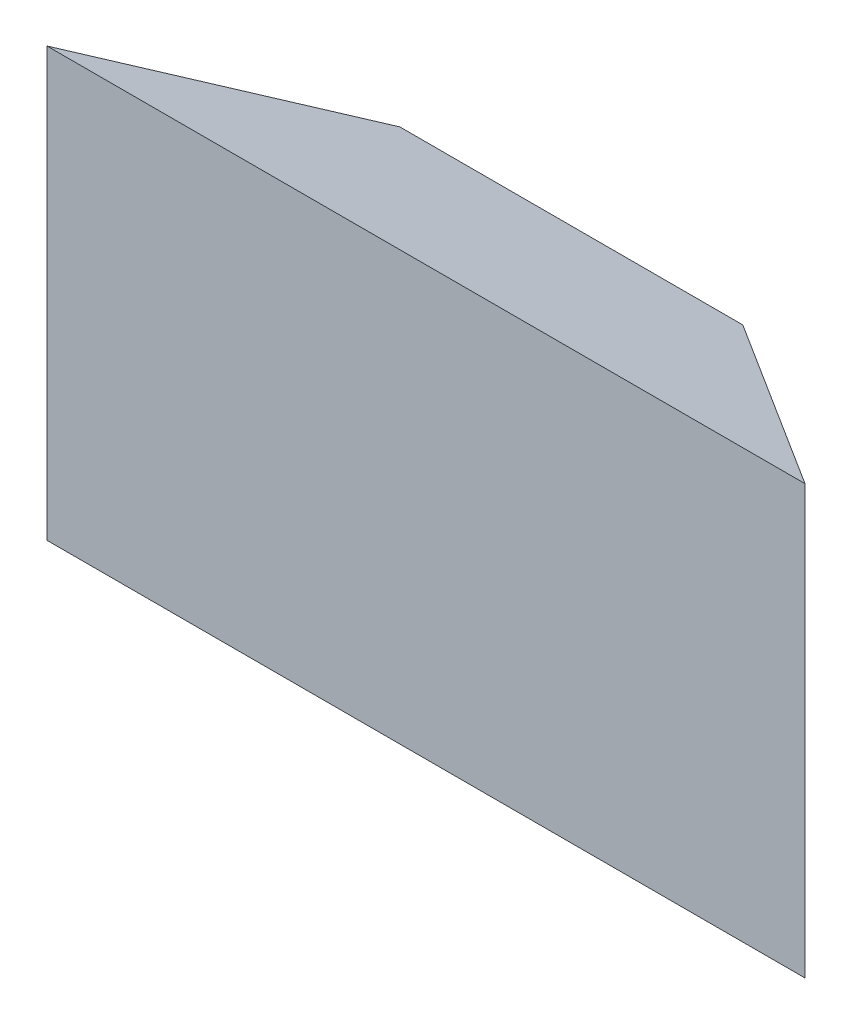
SolidWorks part; units mm, degrees
ref_plane "前视基准面" through (0, 0, 0) normal (0, 0, 1) x (1, 0, 0)
ref_plane "上视基准面" through (0, 0, 0) normal (0, 1, 0) x (1, 0, 0)
ref_plane "右视基准面" through (0, 0, 0) normal (1, 0, 0) x (0, 0, -1)
sketch "草图7" plane through (0, 0, 0) normal (0, 0, 1) x (1, 0, 0)
  line L1 (118, -62.5) -> (-118, -62.5)
  line L2 (118, -62.5) -> (118, 62.5)
  line L3 (118, 62.5) -> (-118, 62.5)
  line L4 (-118, -62.5) -> (-118, 62.5)
  line L5 (118, -62.5) -> (-118, 62.5) construction
  line L6 (118, 62.5) -> (-118, -62.5) construction
  point P0 (0, 0)
  dimension "D1" = 125
  dimension "D2" = 236
extrude "凸台-拉伸7" add sketch "草图7" along normal blind 100 draft 55
sketch "草图9" plane through (0, 0, 0) normal (1, 0, 0) x (0, 0, -1)
  line L0 (0, 62.5) -> (233.1785, 62.5) construction
  line L2 (0, 62.5) -> (-205.9439, 117.6825)
  line L3 (-205.9439, 117.6825) -> (-205.9439, 317.6825)
  line L4 (-205.9439, 317.6825) -> (0, 317.6825)
  line L5 (0, 317.6825) -> (0, 62.5)
  dimension "D1" = 15
  dimension "D2" = 200
  dimension "D3" = 205.9439
extrude "切除-拉伸1" cut sketch "草图9" against normal through all both and the other way through all
sketch "草图1" plane through (0, 0, 0) normal (0, 0, 1) x (1, 0, 0)
  line L0 (0, 0) -> (0, 125)
  line L1 (0, 125) -> (100, 267.8148)
  line L2 (100, 267.8148) -> (100, -26.7949)
  line L3 (100, -26.7949) -> (0, 0)
  dimension "D1" = 105
  dimension "D2" = 145
  dimension "D3" = 125
  dimension "D4" = 100
equation "\"、\"=100"
